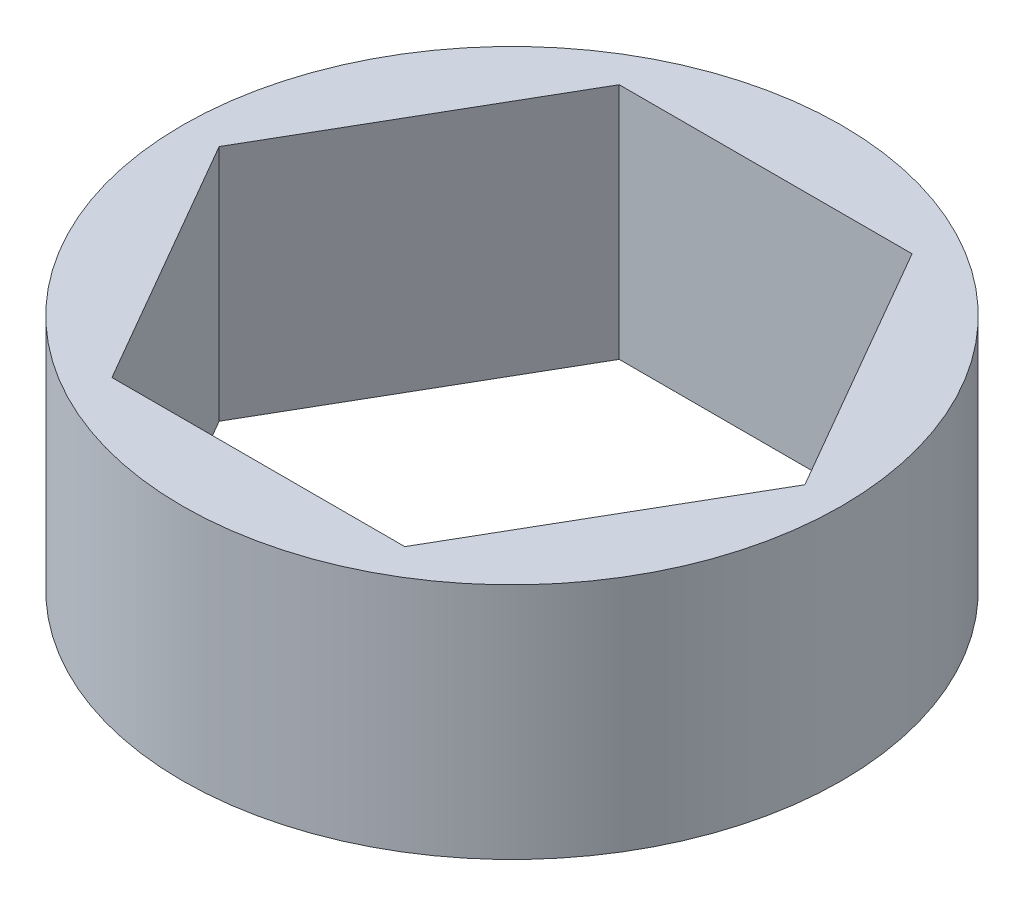
SolidWorks part; units mm, degrees
material "PET"
ref_plane "Front Plane" through (0, 0, 0) normal (0, 0, 1) x (1, 0, 0)
ref_plane "Top Plane" through (0, 0, 0) normal (0, 1, 0) x (1, 0, 0)
ref_plane "Right Plane" through (0, 0, 0) normal (1, 0, 0) x (0, 0, -1)
sketch "Sketch1" plane through (0, 0, 0) normal (0, 1, 0) x (1, 0, 0)
  line L1 (7.3323, 0) -> (3.6662, 6.35)
  line L2 (3.6662, 6.35) -> (-3.6662, 6.35)
  line L3 (-3.6662, 6.35) -> (-7.3323, 0)
  line L4 (-7.3323, 0) -> (-3.6662, -6.35)
  line L5 (-3.6662, -6.35) -> (3.6662, -6.35)
  line L6 (3.6662, -6.35) -> (7.3323, 0)
  circle A0 centre (0, 0) radius 6.35 construction
  circle A1 centre (0, 0) radius 8.255
  dimension "D1" = 16.51
  dimension "D2" = 12.7
extrude "Boss-Extrude1" add sketch "Sketch1" along normal blind 5.9563
